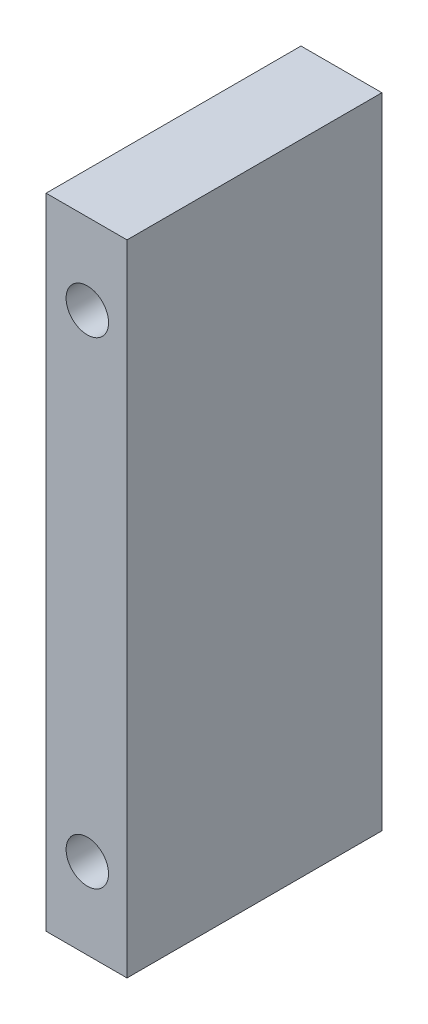
SolidWorks part; units mm, degrees
ref_plane "Front Plane" through (0, 0, 0) normal (1, 0, 0) x (0, 1, 0)
ref_plane "Top Plane" through (0, 0, 0) normal (0, 0, 1) x (0, 1, 0)
ref_plane "Right Plane" through (0, 0, 0) normal (0, 1, 0) x (-1, 0, 0)
sketch "Sketch1" plane through (0, 0, 0) normal (0, 0, 1) x (0, 1, 0)
  line L1 (0, 8) -> (63.2, 8)
  line L2 (0, 8) -> (0, 0)
  line L3 (0, 0) -> (63.2, 0)
  line L4 (63.2, 8) -> (63.2, 0)
  circle A0 centre (8, 3.9243) radius 2.1
  circle A1 centre (55.2, 3.9243) radius 2.1
  dimension "D3" = 4.2
  dimension "D4" = 4.2
  dimension "D1" = 63.2
  dimension "D2" = 8
  dimension "D5" = 8
  dimension "D6" = 8
extrude "Boss-Extrude1" add sketch "Sketch1" along normal blind 25.2
